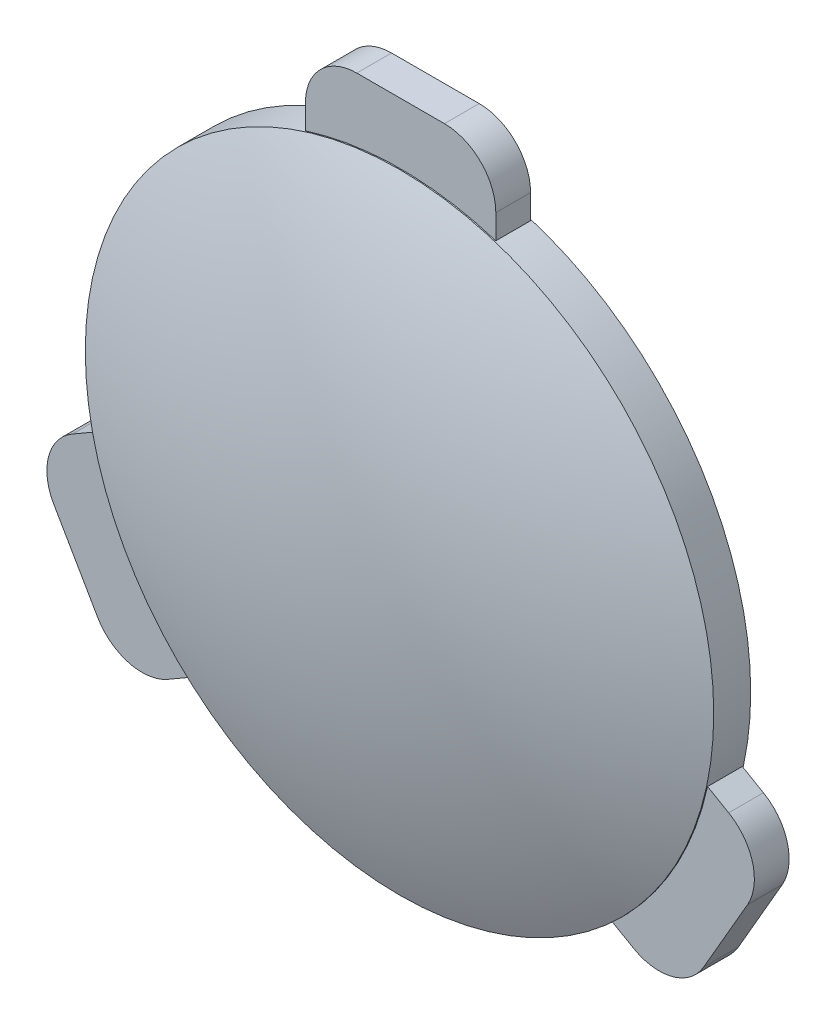
SolidWorks part; units mm, degrees
ref_plane "Front Plane" through (0, 0, 0) normal (0, 0, 1) x (1, 0, 0)
ref_plane "Top Plane" through (0, 0, 0) normal (0, 1, 0) x (1, 0, 0)
ref_plane "Right Plane" through (0, 0, 0) normal (1, 0, 0) x (0, 0, -1)
sketch "Sketch2" plane through (0, 0, 0) normal (1, 0, 0) x (0, 0, -1)
  line L0 (0, 0) -> (17764.6683, 0) construction
  line L1 (-1, 17) -> (1, 17)
  line L2 (0, 17) -> (0, 0) construction
  line L3 (4.3347, 0) -> (-4.4553, 0)
  arc A0 (1, 17) -> (4.3347, 0) centre (-40.6653, 0) cw
  arc A1 (-1, 17) -> (-4.4553, 0) centre (39.0917, 0) ccw
  dimension "D3" = 45
  dimension "D1" = 34
  dimension "D2" = 2
  dimension "D4" = 8.79
revolve "Revolve1" add sketch "Sketch2" angle 360 about L0
sketch "Sketch3" plane through (0, 0, 0) normal (0, 0, 1) x (1, 0, 0)
  line L0 (-5.15, 16.2012) -> (-5.15, 17.52)
  line L1 (-2.37, 20.3) -> (2.37, 20.3)
  line L2 (5.15, 17.52) -> (5.15, 16.2012)
  circle A0 centre (0, 0) radius 17 construction
  arc A1 (5.15, 16.2012) -> (-5.15, 16.2012) centre (0, 0) ccw
  arc A2 (2.37, 20.3) -> (5.15, 17.52) centre (2.37, 17.52) cw
  arc A3 (-5.15, 17.52) -> (-2.37, 20.3) centre (-2.37, 17.52) cw
  point P8 (5.15, 20.3)
  point P11 (-5.15, 20.3)
  dimension "D1" = 3.3
  dimension "D3" = 2.78
  dimension "D2" = 10.3
extrude "Boss-Extrude1" add sketch "Sketch3" along normal mid plane 1.88
pattern_circular "CirPattern1" count 3 over 360 about axis through (0, 0, 0) along (0, 0, 1) of "Boss-Extrude1"
